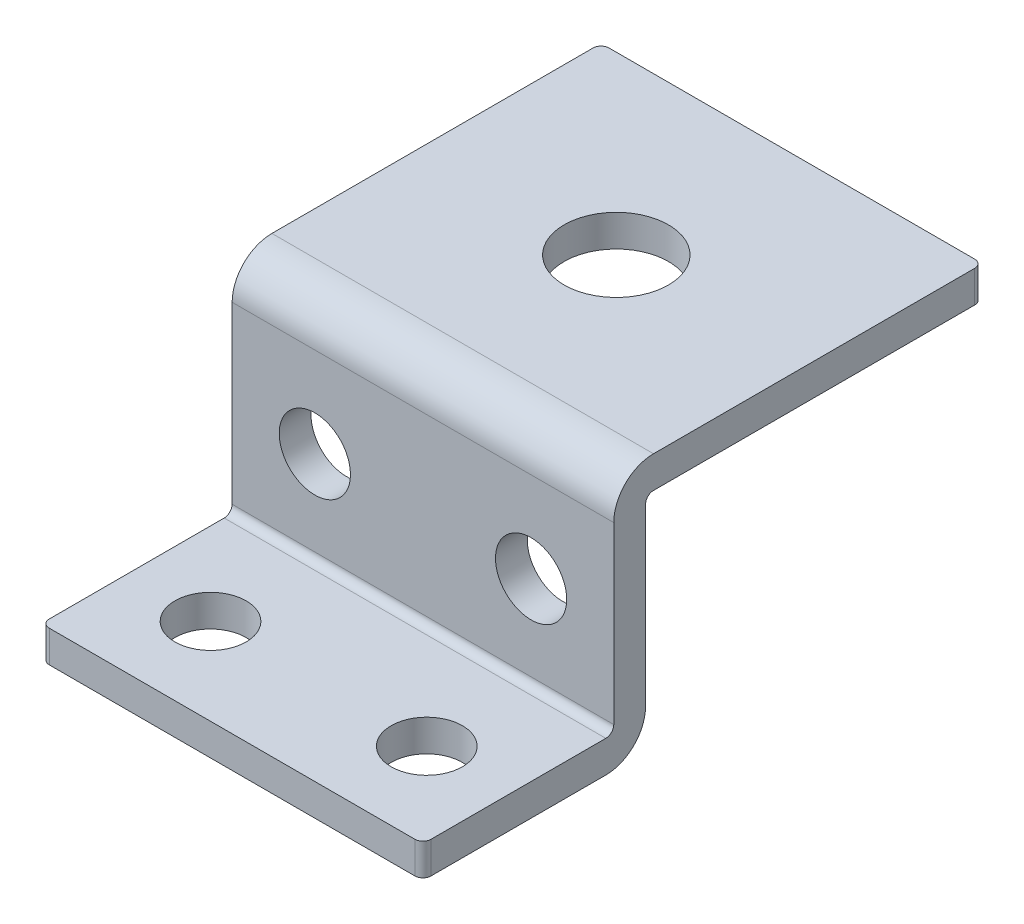
SolidWorks part; units mm, degrees
material "6061-T6 (SS)"
ref_plane "Front Plane" through (0, 0, 0) normal (0, 0, 1) x (1, 0, 0)
ref_plane "Top Plane" through (0, 0, 0) normal (0, 1, 0) x (1, 0, 0)
ref_plane "Right Plane" through (0, 0, 0) normal (1, 0, 0) x (0, 0, -1)
sketch "Sketch1" plane through (0, 0, 0) normal (1, 0, 0) x (0, 0, -1)
  line L0 (-27.94, -9.525) -> (-9.6837, -9.525)
  line L1 (-8.89, -8.7312) -> (-8.89, 8.7312)
  line L2 (-4.9212, 12.7) -> (27.94, 12.7)
  line L3 (-27.94, -12.7) -> (27.94, -12.7) construction
  line L4 (-27.94, -9.525) -> (-27.94, -12.7)
  line L5 (27.94, -12.7) -> (27.94, 12.7) construction
  line L6 (-13.6525, -0.254) -> (-0.9525, -0.254) construction
  arc A0 (-8.89, 8.7312) -> (-4.9212, 12.7) centre (-4.9212, 8.7312) cw
  arc A1 (-9.6837, -9.525) -> (-8.89, -8.7312) centre (-9.6837, -8.7312) ccw
  point P2 (27.94, 0)
  point P10 (-8.89, 12.7)
  point P13 (-8.89, -9.525)
  point P14 (0, -12.7)
  point P17 (-7.3025, -0.254)
  dimension "D1" = 3.9688
  dimension "D2" = 0.7937
  dimension "Offset Length" = 22.225
  dimension "Length B" = 36.83
  dimension "Thickness" = 3.175
  dimension "Length A" = 19.05
  dimension "D3" = 12.7
  dimension "D4" = 12.954
  dimension "D5" = 1.5875
sketch "Sketch2" plane through (0, 0, 0) normal (0, 1, 0) x (1, 0, 0)
  line L0 (-19.05, -8.89) -> (19.05, -8.89) construction
  line L1 (0, -8.89) -> (0, -27.94) construction
  line L2 (0, -4.9212) -> (0, 27.94) construction
  circle A0 centre (10.795, -19.304) radius 3.556
  circle A1 centre (-10.795, -19.304) radius 3.556
  circle A2 centre (0, 10.414) radius 5.207
  circle A3 centre (0, 80.264) radius 5.207 construction
  point P4 (-5.207, 10.414)
  point P14 (-14.351, -19.304)
  dimension "D1" = 7.112
  dimension "D4" = 10.414
  dimension "Length C" = 38.1
  dimension "Front Mount Offset" = 10.414
  dimension "D3" = 21.59
  dimension "Rear Mount Offset 1" = 19.304
  dimension "Rear Mount Offset 2" = 69.85
sketch "Sketch3" plane through (0, 0, 0) normal (0, 0, 1) x (1, 0, 0)
  line L0 (0, 0) -> (0, 8.7312) construction
  line L1 (0, -8.7312) -> (0, 8.7312) construction
  circle A0 centre (-10.795, -0.254) radius 3.556
  circle A1 centre (10.795, -0.254) radius 3.556
  dimension "D1" = 7.112
  dimension "Vert Mount Offset" = 12.954
sketch "Sketch5" plane through (0, 0, 0) normal (1, 0, 0) x (0, 0, -1)
  line L0 (-4.9212, 12.7) -> (27.94, 12.7) construction
  line L1 (-8.89, -8.7312) -> (-8.89, 8.7312) construction
  line L2 (-27.94, -9.525) -> (-9.6837, -9.525) construction
  line L4 (-4.9212, 12.7) -> (27.94, 12.7)
  line L5 (-8.89, -8.7312) -> (-8.89, 8.7312)
  line L6 (-27.94, -9.525) -> (-9.6837, -9.525)
  arc A0 (-4.9212, 12.7) -> (-8.89, 8.7312) centre (-4.9212, 8.7312) ccw construction
  arc A1 (-9.6837, -9.525) -> (-8.89, -8.7312) centre (-9.6837, -8.7312) ccw construction
  arc A2 (-4.9212, 12.7) -> (-8.89, 8.7312) centre (-4.9212, 8.7312) ccw
  arc A3 (-9.6837, -9.525) -> (-8.89, -8.7312) centre (-9.6837, -8.7312) ccw
extrude "Extrude-Thin2" add sketch "Sketch5" along normal mid plane 38.1 thin
sketch "Sketch7" plane through (0, 0, 0) normal (0, 1, 0) x (1, 0, 0)
  circle A0 centre (0, 10.414) radius 5.207 construction
  circle A1 centre (10.795, -19.304) radius 3.556 construction
  circle A2 centre (-10.795, -19.304) radius 3.556 construction
  circle A3 centre (0, 10.414) radius 5.207
  circle A4 centre (10.795, -19.304) radius 3.556
  circle A5 centre (-10.795, -19.304) radius 3.556
extrude "Cut-Extrude1" cut sketch "Sketch7" against normal through all both and the other way through all
sketch "Sketch8" plane through (0, 0, 0) normal (0, 0, 1) x (1, 0, 0)
  circle A0 centre (10.795, -0.254) radius 3.556 construction
  circle A1 centre (-10.795, -0.254) radius 3.556 construction
  circle A2 centre (10.795, -0.254) radius 3.556
  circle A3 centre (-10.795, -0.254) radius 3.556
extrude "Cut-Extrude2" cut sketch "Sketch8" against normal through all both and the other way through all
fillet "Fillet1" radius 0.7937 4 edges at (-19.05, -11.1125, 27.94) (19.05, -11.1125, 27.94) (-19.05, 11.1125, -27.94) (19.05, 11.1125, -27.94)
equation "\"D2@Sketch1\"=\"Thickness@Sketch1\"/4"
equation "\"D1@Sketch1\"=\"Thickness@Sketch1\"+\"D2@Sketch1\""
equation "\"D1@Sketch3\" = \"D1@Sketch2\""
equation "\"D5@Extrude-Thin2\"=\"Thickness@Sketch1\""
equation "\"D1@Extrude-Thin2\" = \"Length C@Sketch2\""
equation "\"D1@Fillet1\"=\"Thickness@Sketch1\"/4"
equation "\"D3@Sketch1\"=\"Thickness@Sketch1\"*4"
equation "\"D4@Sketch1\"=\"Vert Mount Offset@Sketch3\""
equation "\"D5@Sketch1\"=\"Thickness@Sketch1\"/2"
